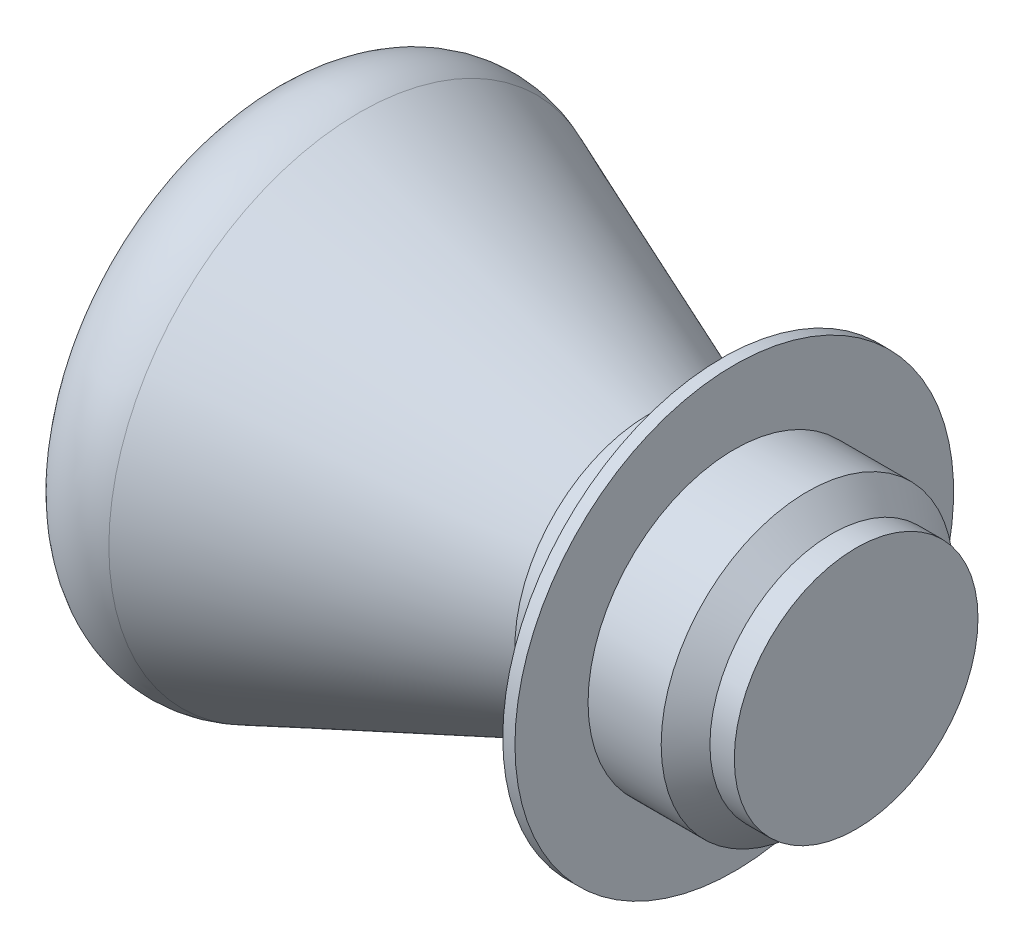
SolidWorks part; units mm, degrees
ref_plane "Płaszczyzna przednia" through (0, 0, 0) normal (0, 0, 1) x (1, 0, 0)
ref_plane "Płaszczyzna górna" through (0, 0, 0) normal (0, 1, 0) x (1, 0, 0)
ref_plane "Płaszczyzna prawa" through (0, 0, 0) normal (1, 0, 0) x (0, 0, -1)
sketch "Szkic1" plane through (0, 0, 0) normal (0, 0, 1) x (1, 0, 0)
  line L0 (0, 0) -> (5.5, 0)
  line L1 (5.5, 0) -> (5.5, 5)
  line L2 (5.5, 5) -> (4.5, 5)
  line L3 (4.5, 5) -> (3.5, 6)
  line L4 (3.5, 6) -> (0.5, 6)
  line L5 (0.5, 6) -> (0.5, 9)
  line L6 (0.5, 9) -> (0, 9)
  line L7 (0, 9) -> (0, 6)
  line L8 (0, 6) -> (-2, 6)
  line L9 (-2, 6) -> (-2, 5.5)
  line L10 (-2, 5.5) -> (0, 5.5)
  line L11 (0, 5.5) -> (0, 0)
  dimension "D1" = 5.5
  dimension "D2" = 5
  dimension "D3" = 1
  dimension "D4" = 1
  dimension "D5" = 1
  dimension "D6" = 3
  dimension "D7" = 0.5
  dimension "D8" = 3
  dimension "D9" = 2
revolve "Obrót1" add sketch "Szkic1" angle 360 about L0
sketch "Szkic2" plane through (0, 0, 0) normal (0, 0, 1) x (1, 0, 0)
  line L0 (0, 0) -> (-18.3873, 0) construction
  line L1 (0, 0) -> (0, 5.5)
  line L2 (0, 5.5) -> (-3, 5.5)
  line L3 (-3, 5.5) -> (-14.8796, 10.2829)
  line L4 (-18.3873, 0) -> (0, 0)
  arc A0 (-18.9584, 7.9981) -> (-18.3873, 0) centre (-2.1943, 5.1756) ccw
  arc A1 (-14.8796, 10.2829) -> (-18.9584, 7.9981) centre (-16, 7.5) ccw
  point P8 (-11.2756, 7.2398)
  point P11 (0, 0)
  point P12 (0, 0)
  point P13 (-16, 6.6897)
  dimension "D1" = 3
  dimension "D4" = 17
  dimension "D2" = 16
  dimension "D3" = 2
  dimension "D5" = 3
revolve "Obrót2" add sketch "Szkic2" angle 360 about L4
